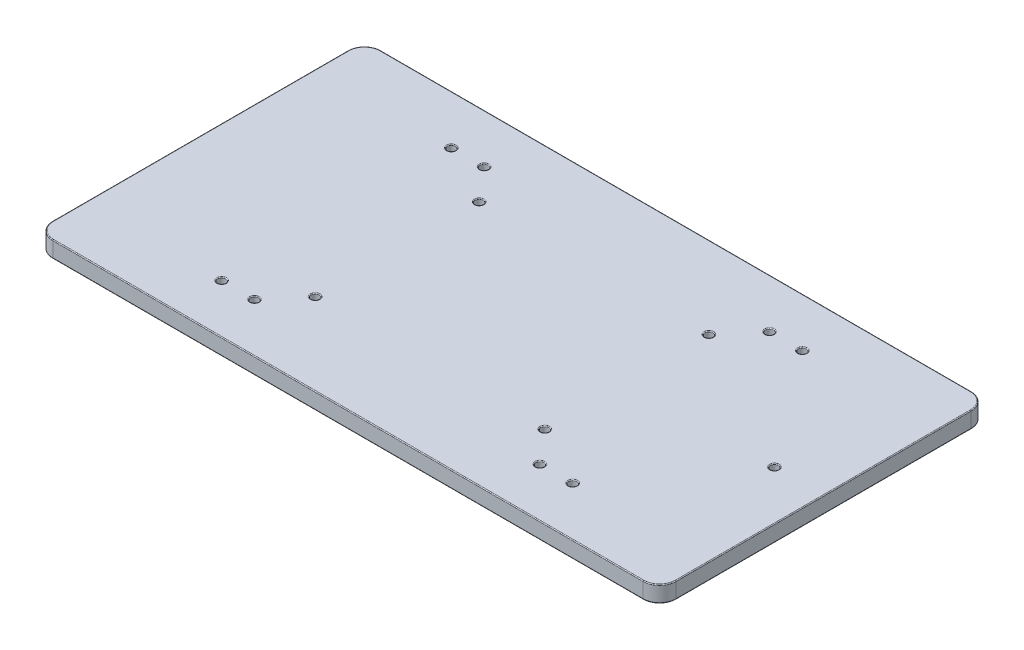
SolidWorks part; units mm, degrees
ref_plane "Front Plane" through (0, 0, 0) normal (0, 0, 1) x (1, 0, 0)
ref_plane "Top Plane" through (0, 0, 0) normal (0, 1, 0) x (1, 0, 0)
ref_plane "Right Plane" through (0, 0, 0) normal (1, 0, 0) x (0, 0, -1)
sketch "Sketch1" plane through (0, 0, 0) normal (0, 1, 0) x (1, 0, 0)
  line L0 (80, 50) -> (80, -50) construction
  line L1 (-95, 50) -> (95, 50)
  line L2 (-95, 50) -> (-95, -50)
  line L3 (-95, -50) -> (95, -50)
  line L4 (95, 50) -> (95, -50)
  line L5 (-95, 50) -> (95, -50) construction
  line L6 (-95, -50) -> (95, 50) construction
  line L7 (-35, 25) -> (35, 25) construction
  line L8 (-35, 25) -> (-35, -25) construction
  line L9 (-35, -25) -> (35, -25) construction
  line L10 (35, 25) -> (35, -25) construction
  line L11 (-35, 25) -> (35, -25) construction
  line L12 (-35, -25) -> (35, 25) construction
  line L13 (0, 0) -> (35, 0) construction
  line L14 (0, 0) -> (0, 25) construction
  circle A0 centre (-35, 25) radius 1.25
  circle A1 centre (35, 25) radius 1.25
  circle A2 centre (35, -25) radius 1.25
  circle A3 centre (-35, -25) radius 1.25
  circle A5 centre (80, 0) radius 1.25
  circle A6 centre (-53.5, -35) radius 1.25
  circle A7 centre (-43.5, -35) radius 1.25
  circle A8 centre (-53.5, 35) radius 1.25
  circle A9 centre (-43.5, 35) radius 1.25
  circle A10 centre (53.5, -35) radius 1.25
  circle A11 centre (43.5, -35) radius 1.25
  circle A12 centre (53.5, 35) radius 1.25
  circle A13 centre (43.5, 35) radius 1.25
  point P0 (0, 0)
  point P6 (0, 0)
  dimension "D5" = 2.5
  dimension "D7" = 2.5
  dimension "D1" = 190
  dimension "D2" = 100
  dimension "D3" = 70
  dimension "D4" = 50
  dimension "D6" = 15
  dimension "D8" = 43.5
  dimension "D9" = 10
  dimension "D10" = 15
extrude "Boss-Extrude1" add sketch "Sketch1" along normal blind 5
fillet "Fillet1" radius 5 4 edges at (-95, 2.5, 50) (-95, 2.5, -50) (95, 2.5, -50) (95, 2.5, 50)
fillet "Fillet2" radius 0.25 42 edges at (43.5, 0, -33.75) (43.5, 5, -33.75) (53.5, 0, -33.75) (53.5, 5, -33.75) (43.5, 0, 33.75) (43.5, 5, 33.75) (53.5, 0, 33.75) (53.5, 5, 33.75) (-43.5, 0, -36.25) (-43.5, 5, -36.25) (-53.5, 0, -36.25) (-53.5, 5, -36.25) (-43.5, 0, 36.25) (-43.5, 5, 36.25) (-53.5, 0, 36.25) (-53.5, 5, 36.25) (80, 0, 1.25) (80, 5, 1.25) (-35, 0, 26.25) (-35, 5, 26.25) (35, 0, 26.25) (35, 5, 26.25) (35, 0, -23.75) (35, 5, -23.75) (-35, 0, -23.75) (-35, 5, -23.75) (95, 0, 0) (0, 0, -50) (-95, 0, 0) (0, 0, 50) (95, 5, 0) (0, 5, -50) (-95, 5, 0) (93.5355, 0, 48.5355) (93.5355, 0, -48.5355) (-93.5355, 0, -48.5355) (-93.5355, 0, 48.5355) (93.5355, 5, 48.5355) (93.5355, 5, -48.5355) (-93.5355, 5, -48.5355) (-93.5355, 5, 48.5355) (0, 5, 50)
